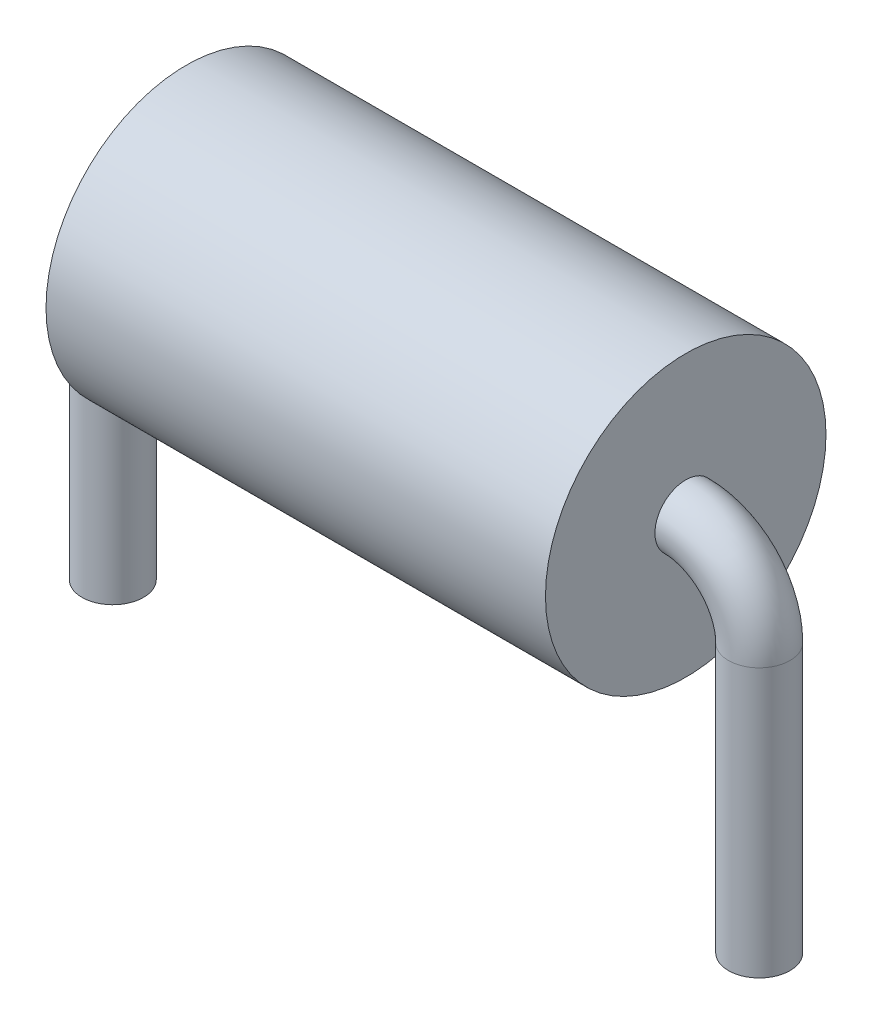
SolidWorks part; units mm, degrees
ref_plane "Front Plane" through (0, 0, 0) normal (0, 0, 1) x (1, 0, 0)
ref_plane "Top Plane" through (0, 0, 0) normal (0, 1, 0) x (1, 0, 0)
ref_plane "Right Plane" through (0, 0, 0) normal (1, 0, 0) x (0, 0, -1)
sketch "Sketch1" plane through (0, 0, 0) normal (1, 0, 0) x (0, 0, -1)
  circle A0 centre (0, 0) radius 2.6035
  dimension "D1" = 5.207
extrude "Boss-Extrude1" add sketch "Sketch1" along normal mid plane 9.271 contours A0
sketch "Sketch2" plane through (0, 0, 0) normal (0, 0, 1) x (1, 0, 0)
  line L0 (-6, -6.35) -> (-6, -1.3645)
  line L1 (-4.6355, 0) -> (4.6355, 0)
  line L2 (6, -1.3645) -> (6, -6.35)
  line L3 (4.6355, -2.6035) -> (4.6355, 2.6035) construction
  line L4 (-4.6355, 2.6035) -> (-4.6355, -2.6035) construction
  arc A0 (6, -1.3645) -> (4.6355, 0) centre (4.6355, -1.3645) ccw
  arc A1 (-6, -1.3645) -> (-4.6355, 0) centre (-4.6355, -1.3645) cw
  point P8 (0, 0)
  point P14 (7.1755, -6.242)
  dimension "D1" = 12
  dimension "D2" = 6.35
ref_plane "Plane1" through (-6, -6.35, 0) normal (0, 1, 0) x (1, 0, 0)
sketch "Sketch3" plane through (-6, -6.35, 0) normal (0, 1, 0) x (1, 0, 0)
  line L0 (0, 0) -> (1.3645, 0) construction
  circle A0 centre (0, 0) radius 0.5715
  point P4 (0.4125, 0)
  dimension "D1" = 1.143
sweep "Sweep1" add profiles "Sketch3" path "Sketch2"
